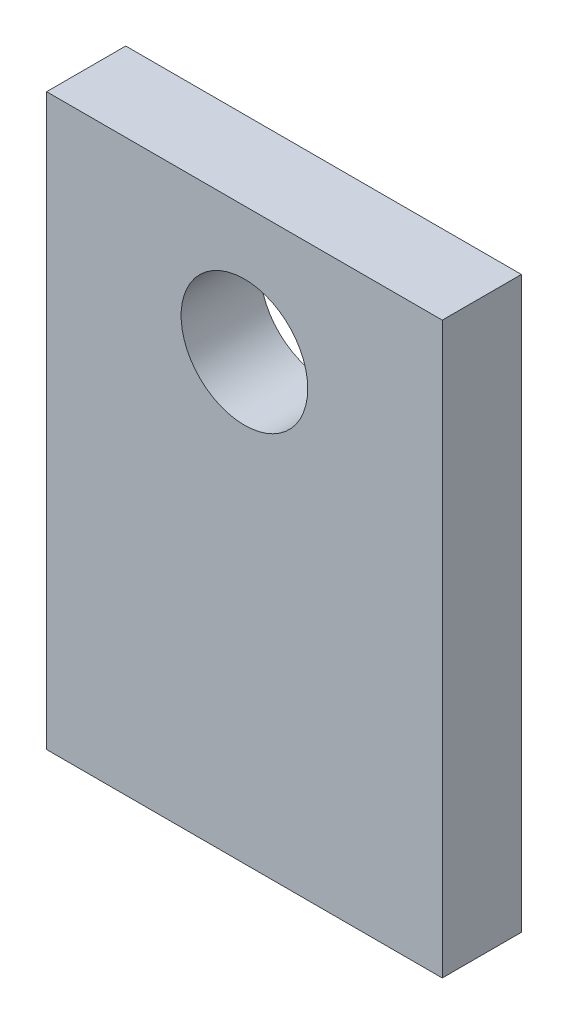
SolidWorks part; units mm, degrees
ref_plane "Front" through (0, 0, 0) normal (0, 0, 1) x (1, 0, 0)
ref_plane "Top" through (0, 0, 0) normal (0, 1, 0) x (1, 0, 0)
ref_plane "Right" through (0, 0, 0) normal (1, 0, 0) x (0, 0, -1)
sketch "Sketch1" plane through (0, 0, 0) normal (0, 0, 1) x (1, 0, 0)
  line L1 (0, 0) -> (125, 0)
  line L2 (0, 0) -> (0, 180)
  line L3 (0, 180) -> (125, 180)
  line L4 (125, 0) -> (125, 180)
  circle A0 centre (62.5, 140) radius 20
  dimension "D3" = 40
  dimension "D5" = 40
  dimension "D1" = 125
  dimension "D2" = 180
  dimension "D4" = 62.5
extrude "Base-Extrude" add sketch "Sketch1" along normal blind 25
